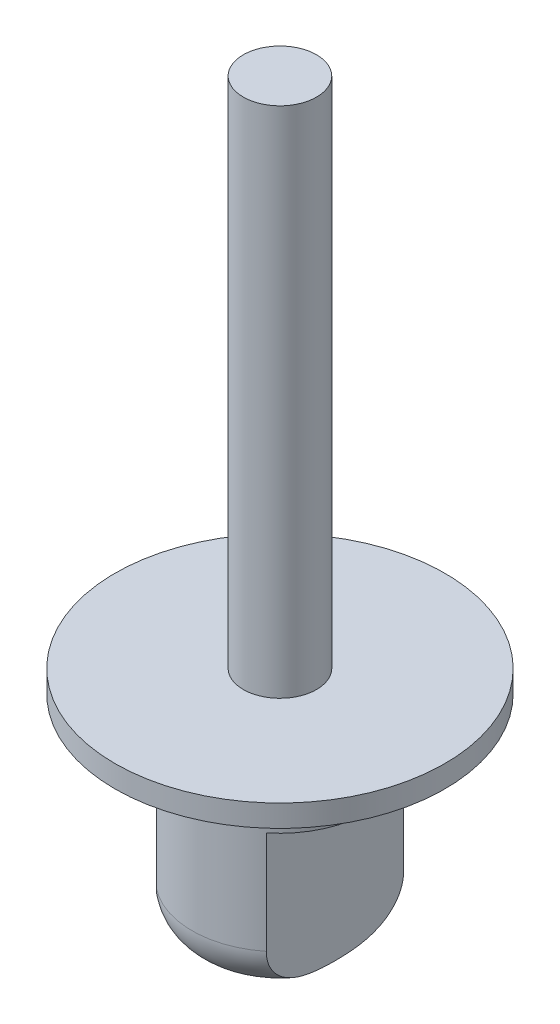
SolidWorks part; units mm, degrees
ref_plane "Front Plane" through (0, 0, 0) normal (0, 0, 1) x (1, 0, 0)
ref_plane "Top Plane" through (0, 0, 0) normal (0, 1, 0) x (1, 0, 0)
ref_plane "Right Plane" through (0, 0, 0) normal (1, 0, 0) x (0, 0, -1)
sketch "Sketch1" plane through (0, 0, 0) normal (0, 1, 0) x (1, 0, 0)
  circle A0 centre (0, 0) radius 22.5
  dimension "D1" = 45
extrude "Boss-Extrude1" add sketch "Sketch1" along normal blind 3 contours A0
sketch "Sketch2" plane through (0, 3, 0) normal (0, 1, 0) x (1, 0, 0)
  circle A0 centre (0, 0) radius 5
  dimension "D1" = 10
extrude "Boss-Extrude2" add sketch "Sketch2" along normal blind 70 contours A0
sketch "Sketch3" plane through (0, 0, 0) normal (0, -1, 0) x (1, 0, 0)
  circle A0 centre (0, 0) radius 12
  dimension "D1" = 24
extrude "Boss-Extrude3" add sketch "Sketch3" along normal blind 28 contours A0
fillet "Fillet1" radius 6 1 edges at (0, -28, -12)
sketch "Sketch4" plane through (0, 0, 0) normal (0, 0, 1) x (1, 0, 0)
  line L0 (0, 0) -> (0, -28) construction
  line L1 (-6, -28) -> (6, -28) construction
  line L2 (7.5, -8) -> (7.5, -28)
  line L3 (7.5, -28) -> (27.07, -28)
  line L4 (27.07, -28) -> (27.07, -8)
  line L5 (27.07, -8) -> (7.5, -8)
  line L6 (-27.07, -8) -> (-7.5, -8)
  line L7 (-27.07, -28) -> (-27.07, -8)
  line L8 (-7.5, -28) -> (-27.07, -28)
  line L9 (-7.5, -8) -> (-7.5, -28)
  dimension "D1" = 20
  dimension "D2" = 15
  dimension "D3" = 19.57
extrude "Cut-Extrude1" cut sketch "Sketch4" against normal through all both and the other way through all
